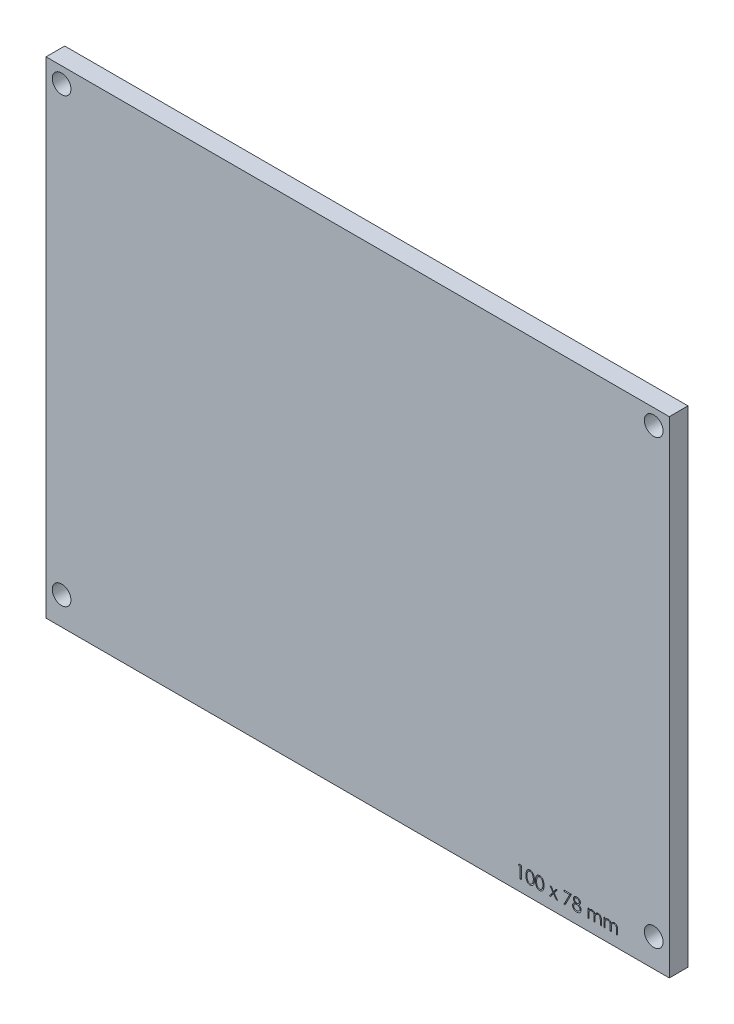
SolidWorks part; units mm, degrees
ref_plane "Front Plane" through (0, 0, 0) normal (0, 0, 1) x (1, 0, 0)
ref_plane "Top Plane" through (0, 0, 0) normal (0, 1, 0) x (1, 0, 0)
ref_plane "Right Plane" through (0, 0, 0) normal (1, 0, 0) x (0, 0, -1)
sketch "Sketch1" plane through (0, 0, 0) normal (0, 0, 1) x (1, 0, 0)
  line L1 (-50, 39) -> (50, 39)
  line L2 (-50, 39) -> (-50, -39)
  line L3 (-50, -39) -> (50, -39)
  line L4 (50, 39) -> (50, -39)
  line L5 (-50, 39) -> (50, -39) construction
  line L6 (-50, -39) -> (50, 39) construction
  dimension "D1" = 78
  dimension "D2" = 100
  dimension "D3" = 39
  dimension "D4" = 50
extrude "Boss-Extrude1" add sketch "Sketch1" along normal blind 3 contours L1 L4 L3 L2
sketch "Sketch2" plane through (0, 0, 3) normal (0, 0, 1) x (1, 0, 0)
  line L1 (0, -1.65) -> (0, 1.65) construction
  line L3 (50, 39) -> (50, -39) construction
  line L6 (-50, -39) -> (50, -39) construction
  line L7 (-50, 39) -> (50, 39) construction
  line L9 (-50, 39) -> (-50, -39) construction
  circle A0 centre (-47.5, 36.5) radius 1.5
  circle A4 centre (47.5, 36.5) radius 1.5
  circle A5 centre (47.5, -34.5) radius 1.5
  circle A6 centre (-47.5, -34.5) radius 1.5
  dimension "D1" = 3
  dimension "D2" = 1
  dimension "D3" = 1
  dimension "D4" = 3
  dimension "D5" = 3
  dimension "D6" = 1
  dimension "D7" = 1
  dimension "D8" = 1
  dimension "D9" = 3
extrude "Cut-Extrude1" cut sketch "Sketch2" against normal through all both and the other way through all
sketch "Sketch4" plane through (0, 0, 3) normal (0, 0, 1) x (1, 0, 0)
  text T0 "100 x 78 mm\r\n" font "Century Gothic" height 2
extrude "Cut-Extrude2" cut sketch "Sketch4" against normal blind 1
